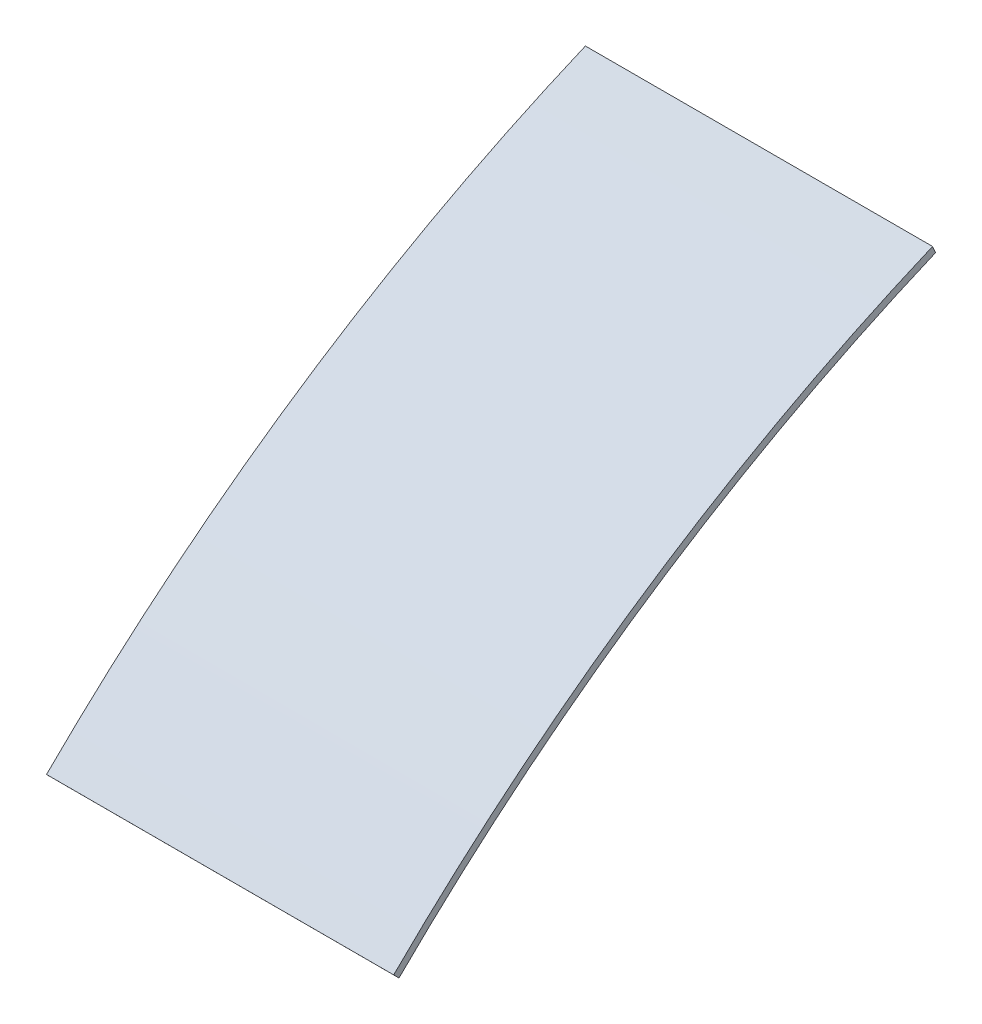
SolidWorks part; units mm, degrees
material "Acrylic (Medium-high impact)"
ref_plane "Front Plane" through (0, 0, 0) normal (0, 0, 1) x (1, 0, 0)
ref_plane "Top Plane" through (0, 0, 0) normal (0, 1, 0) x (1, 0, 0)
ref_plane "Right Plane" through (0, 0, 0) normal (1, 0, 0) x (0, 0, -1)
sketch "Sketch1" plane through (0, 0, 0) normal (1, 0, 0) x (0, 0, -1)
  line L0 (-224.691, -154.4506) -> (-226.9302, -152.1996)
  line L5 (0, 0) -> (1.2332, -2.9257)
  arc A0 (0, 0) -> (-226.9302, -152.1996) centre (278.0348, -659.8276) ccw
  arc A1 (1.2332, -2.9257) -> (-224.691, -154.4506) centre (278.0348, -659.8276) ccw
  arc A2 (0.6166, -1.4629) -> (-225.8106, -153.3251) centre (278.0348, -659.8276) ccw
  dimension "D3" = 714.4263
  dimension "D1" = 3.175
  dimension "D2" = 274.32
extrude "Boss-Extrude1" add sketch "Sketch1" along normal mid plane 146.2024 contours L5 A2 L0 A1 | A2 L5 A0 L0
sketch "Sketch2" plane through (-73.1012, 0, 0) normal (-1, 0, 0) x (0, 0, 1)
  line L2 (-1.4789, -3.5086) -> (0.2457, 0.5829)
  line L3 (6.0971, -1.8835) -> (4.3725, -5.9751)
  line L4 (-1.4789, -3.5086) -> (4.3725, -5.9751)
  line L5 (6.0971, -1.8835) -> (0.2457, 0.5829)
  line L6 (0, 0) -> (-1.2332, -2.9257) construction
  point P11 (-0.6166, -1.4629)
  point P12 (-0.6166, -1.4629)
  dimension "D1" = 6.35
extrude "Cut-Extrude1" [suppressed] cut sketch "Sketch2" against normal through all
equation "\"WallThickness\"=0.125"
equation "\"D1\"= \"WallThickness\""
equation "\"D1@Sketch1\"=\"WallThickness\""
